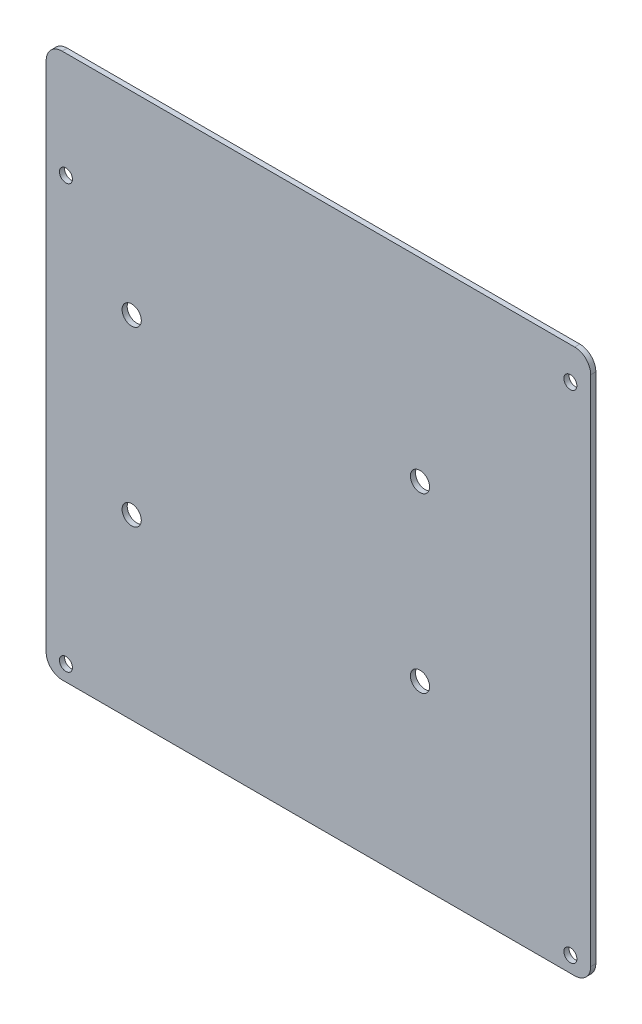
SolidWorks part; units mm, degrees
material "Epoxy, Unfilled"
ref_plane "Front Plane" through (0, 0, 0) normal (0, 0, 1) x (1, 0, 0)
ref_plane "Top Plane" through (0, 0, 0) normal (0, 1, 0) x (1, 0, 0)
ref_plane "Right Plane" through (0, 0, 0) normal (1, 0, 0) x (0, 0, -1)
sketch "Sketch1" plane through (0, 0, 0) normal (0, 0, 1) x (1, 0, 0)
  line L1 (85, -85) -> (-85, -85)
  line L2 (85, -85) -> (85, 85)
  line L3 (85, 85) -> (-85, 85)
  line L4 (-85, -85) -> (-85, 85)
  line L5 (85, -85) -> (-85, 85) construction
  line L6 (85, 85) -> (-85, -85) construction
  point P0 (0, 0)
  dimension "D1" = 170
  dimension "D2" = 170
extrude "Base" add sketch "Sketch1" along normal blind 1.6
fillet "Rounding corners" radius 5 4 edges at (-85, 85, 0.8) (85, 85, 0.8) (85, -85, 0.8) (-85, -85, 0.8)
sketch "Sketch2" plane through (0, 0, 1.6) normal (0, 0, 1) x (1, 0, 0)
  line L0 (85, -80) -> (85, 80) construction
  line L1 (80, 85) -> (-80, 85) construction
  circle A0 centre (-78.83, 51.98) radius 2.03
  circle A1 centre (78.65, 74.84) radius 2.03
  circle A2 centre (-78.83, -80.1) radius 2.03
  circle A3 centre (78.65, -80.1) radius 2.03
  dimension "D1" = 4.06
  dimension "D2" = 4.06
  dimension "D3" = 4.06
  dimension "D4" = 4.06
  dimension "D5" = 157.48
  dimension "D6" = 22.86
  dimension "D7" = 6.35
  dimension "D8" = 10.16
  dimension "D9" = 154.94
  dimension "D10" = 6.35
  dimension "D11" = 157.48
  dimension "D12" = 0
extrude "Mounting holes" cut sketch "Sketch2" against normal blind 1.6
sketch "Sketch4" plane through (0, 0, 1.6) normal (0, 0, 1) x (1, 0, 0)
  line L0 (-85, 80) -> (-85, -80) construction
  line L1 (-80, -85) -> (80, -85) construction
  circle A0 centre (-58.3, 24.5) radius 3
  circle A1 centre (31.7, 24.5) radius 3
  circle A2 centre (31.7, -29.5) radius 3
  circle A3 centre (-58.3, -29.5) radius 3
  dimension "D1" = 6
  dimension "D2" = 6
  dimension "D3" = 6
  dimension "D4" = 6
  dimension "D5" = 90
  dimension "D6" = 26.7
  dimension "D7" = 54
  dimension "D8" = 26.7
  dimension "D9" = 55.5
  dimension "D10" = 90
  dimension "D11" = 54
  dimension "D12" = 55.5
extrude "Cooler holes" cut sketch "Sketch4" against normal blind 1.6
